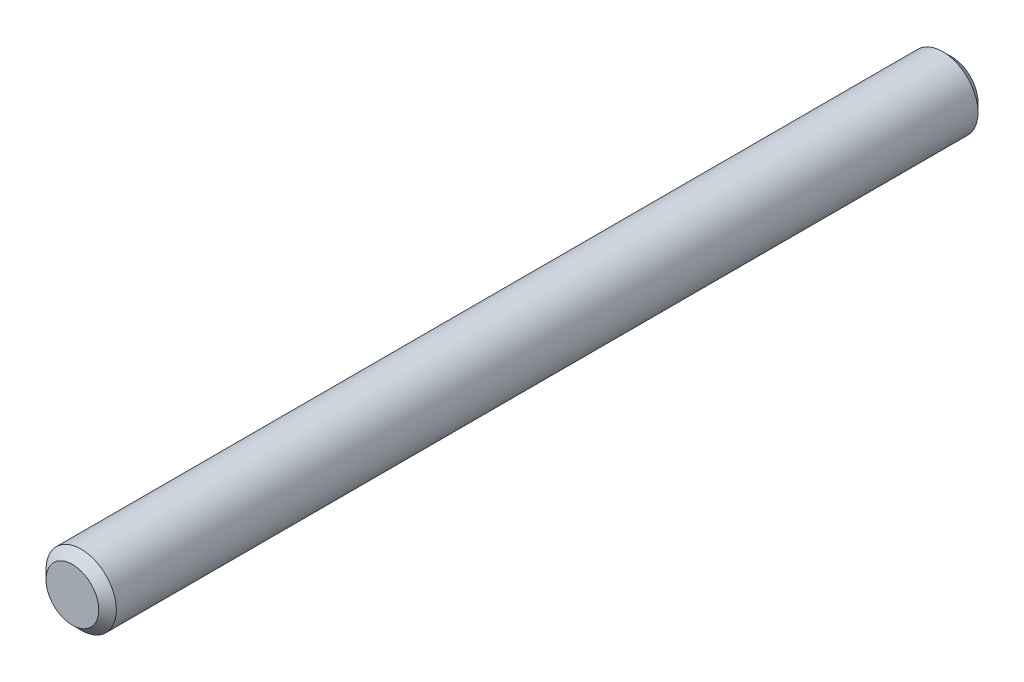
SolidWorks part; units mm, degrees
ref_plane "Front Plane" through (0, 0, 0) normal (0, 0, 1) x (1, 0, 0)
ref_plane "Top Plane" through (0, 0, 0) normal (0, 1, 0) x (1, 0, 0)
ref_plane "Right Plane" through (0, 0, 0) normal (1, 0, 0) x (0, 0, -1)
sketch "Sketch1" plane through (0, 0, 0) normal (0, 0, 1) x (1, 0, 0)
  circle A0 centre (0, 0) radius 4
  dimension "D1" = 8
extrude "Boss-Extrude1" add sketch "Sketch1" along normal blind 100
chamfer "Chamfer1" distance 1 angle 45 2 edges at (4, 0, 100) (4, 0, 0)
